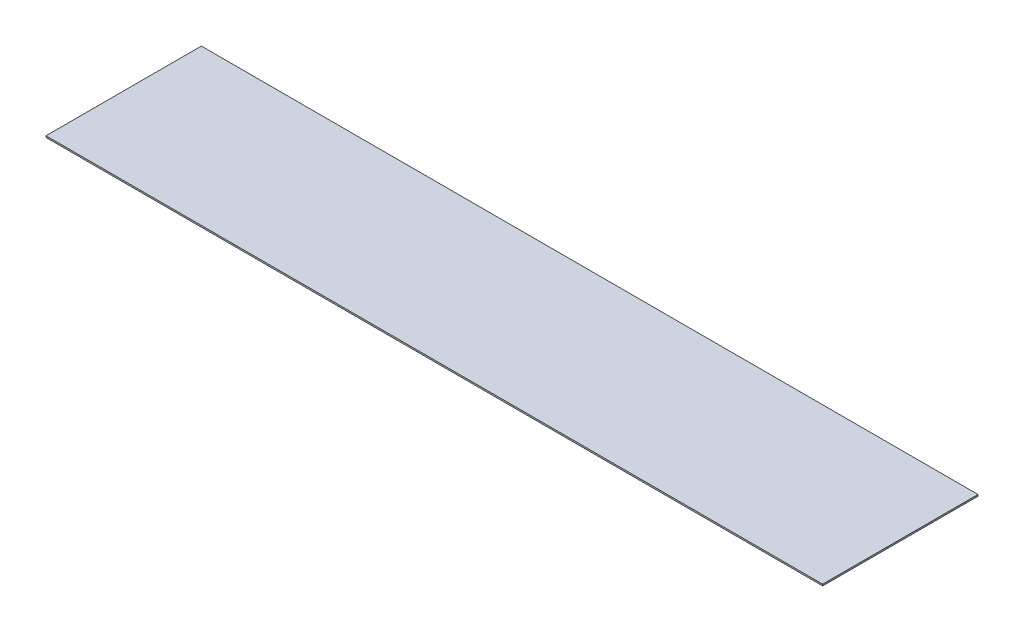
SolidWorks part; units mm, degrees
material "AISI 1020"
ref_plane "Plan de face" through (0, 0, 0) normal (0, 0, 1) x (1, 0, 0)
ref_plane "Plan de dessus" through (0, 0, 0) normal (0, 1, 0) x (1, 0, 0)
ref_plane "Plan de droite" through (0, 0, 0) normal (1, 0, 0) x (0, 0, -1)
sketch "Esquisse1" plane through (0, 0, 0) normal (0, 1, 0) x (1, 0, 0)
  line L1 (-635, -127) -> (635, -127)
  line L2 (-635, -127) -> (-635, 127)
  line L3 (-635, 127) -> (635, 127)
  line L4 (635, -127) -> (635, 127)
  line L5 (-635, -127) -> (635, 127) construction
  line L6 (-635, 127) -> (635, -127) construction
  point P0 (0, 0)
  dimension "D1" = 1270
  dimension "D2" = 254
extrude "Boss.-Extru.1" add sketch "Esquisse1" along normal blind 2.54
